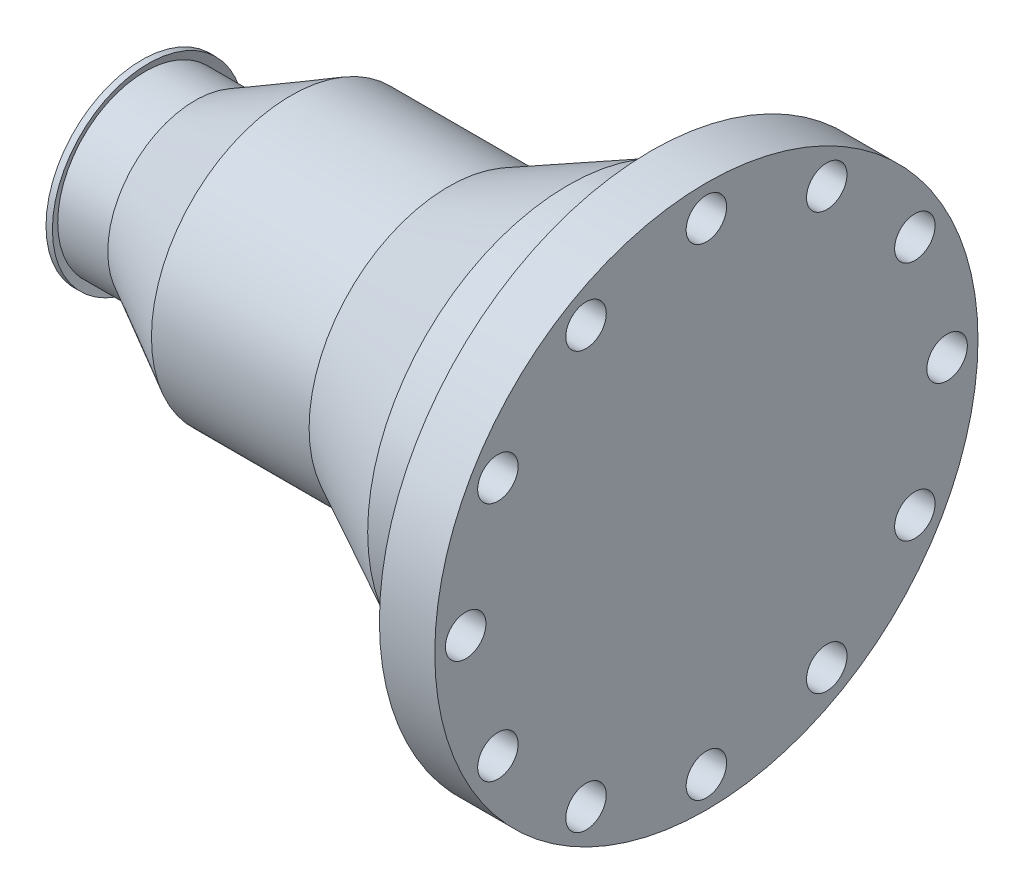
SolidWorks part; units mm, degrees
ref_plane "Спереди" through (0, 0, 0) normal (0, 0, 1) x (1, 0, 0)
ref_plane "Сверху" through (0, 0, 0) normal (0, 1, 0) x (1, 0, 0)
ref_plane "Справа" through (0, 0, 0) normal (1, 0, 0) x (0, 0, -1)
sketch "Эскиз1" plane through (0, 0, 0) normal (0, 0, 1) x (1, 0, 0)
  line L0 (0, 0) -> (265, 0)
  line L1 (0, 0) -> (0, 45)
  line L2 (0, 45) -> (3, 45)
  line L3 (3, 45) -> (1.5, 41)
  line L4 (1.5, 41) -> (25, 41)
  line L5 (25, 41) -> (70, 65.5)
  line L6 (70, 65.5) -> (144, 65.5)
  line L7 (144, 65.5) -> (200, 94)
  line L8 (200, 94) -> (220, 94)
  line L9 (220, 94) -> (220, 95)
  line L10 (220, 95) -> (239, 95)
  line L11 (239, 95) -> (239, 100)
  line L12 (239, 100) -> (239, 127.5)
  line L13 (239, 127.5) -> (265, 127.5)
  line L14 (265, 127.5) -> (265, 0)
revolve "Повернуть1" add sketch "Эскиз1" angle 360 about L0
sketch "Эскиз2" plane through (0, 0, 0) normal (0, 0, 1) x (1, 0, 0)
  line L0 (0, 0) -> (215.8313, 0)
  line L1 (0, 0) -> (0, 31)
  line L2 (0, 45) -> (0, -45) construction
  line L3 (0, 31) -> (42, 31)
  line L4 (42, 31) -> (115.8904, 50.7963)
  line L5 (128.8303, 52.5835) -> (133.8313, 52.5835)
  line L6 (133.8313, 52.5835) -> (215.8313, 52.5835)
  line L7 (215.8313, 52.5835) -> (215.8313, 0)
  arc A0 (115.8904, 50.7963) -> (128.8303, 52.5835) centre (129.4994, 0) cw
revolve "Вырез-Повернуть1" cut sketch "Эскиз2" angle 360 about L0
sketch "Эскиз3" plane through (0, 0, 0) normal (1, 0, 0) x (0, 0, -1)
  circle A0 centre (0, 113) radius 9.5
extrude "Вырез-Вытянуть1" cut sketch "Эскиз3" along normal through all
sketch "Эскиз4" plane through (0, 0, 0) normal (1, 0, 0) x (0, 0, -1)
  circle A0 centre (-56.5, 97.8609) radius 9.5
extrude "Вырез-Вытянуть2" cut sketch "Эскиз4" along normal through all
sketch "Эскиз5" plane through (0, 0, 0) normal (1, 0, 0) x (0, 0, -1)
  circle A0 centre (-97.8609, 56.5) radius 9.5
extrude "Вырез-Вытянуть3" cut sketch "Эскиз5" along normal through all
sketch "Эскиз6" plane through (0, 0, 0) normal (1, 0, 0) x (0, 0, -1)
  circle A0 centre (-113, 0) radius 9.5
extrude "Вырез-Вытянуть4" cut sketch "Эскиз6" along normal through all
sketch "Эскиз7" plane through (0, 0, 0) normal (1, 0, 0) x (0, 0, -1)
  circle A0 centre (-97.8609, -56.5) radius 9.5
extrude "Вырез-Вытянуть5" cut sketch "Эскиз7" along normal through all
sketch "Эскиз8" plane through (0, 0, 0) normal (1, 0, 0) x (0, 0, -1)
  circle A0 centre (-56.5, -97.8609) radius 9.5
extrude "Вырез-Вытянуть6" cut sketch "Эскиз8" along normal through all
sketch "Эскиз9" plane through (0, 0, 0) normal (1, 0, 0) x (0, 0, -1)
  circle A0 centre (0, -113) radius 9.5
extrude "Вырез-Вытянуть7" cut sketch "Эскиз9" along normal through all
sketch "Эскиз10" plane through (0, 0, 0) normal (1, 0, 0) x (0, 0, -1)
  circle A0 centre (56.5, -97.8609) radius 9.5
extrude "Вырез-Вытянуть8" cut sketch "Эскиз10" along normal through all
sketch "Эскиз11" plane through (0, 0, 0) normal (1, 0, 0) x (0, 0, -1)
  circle A0 centre (97.8609, -56.5) radius 9.5
extrude "Вырез-Вытянуть9" cut sketch "Эскиз11" along normal through all
sketch "Эскиз12" plane through (0, 0, 0) normal (1, 0, 0) x (0, 0, -1)
  circle A0 centre (113, 0) radius 9.5
extrude "Вырез-Вытянуть10" cut sketch "Эскиз12" along normal through all
sketch "Эскиз13" plane through (0, 0, 0) normal (1, 0, 0) x (0, 0, -1)
  circle A0 centre (97.8609, 56.5) radius 9.5
extrude "Вырез-Вытянуть11" cut sketch "Эскиз13" along normal through all
sketch "Эскиз14" plane through (0, 0, 0) normal (1, 0, 0) x (0, 0, -1)
  circle A0 centre (56.5, 97.8609) radius 9.5
extrude "Вырез-Вытянуть12" cut sketch "Эскиз14" along normal through all
